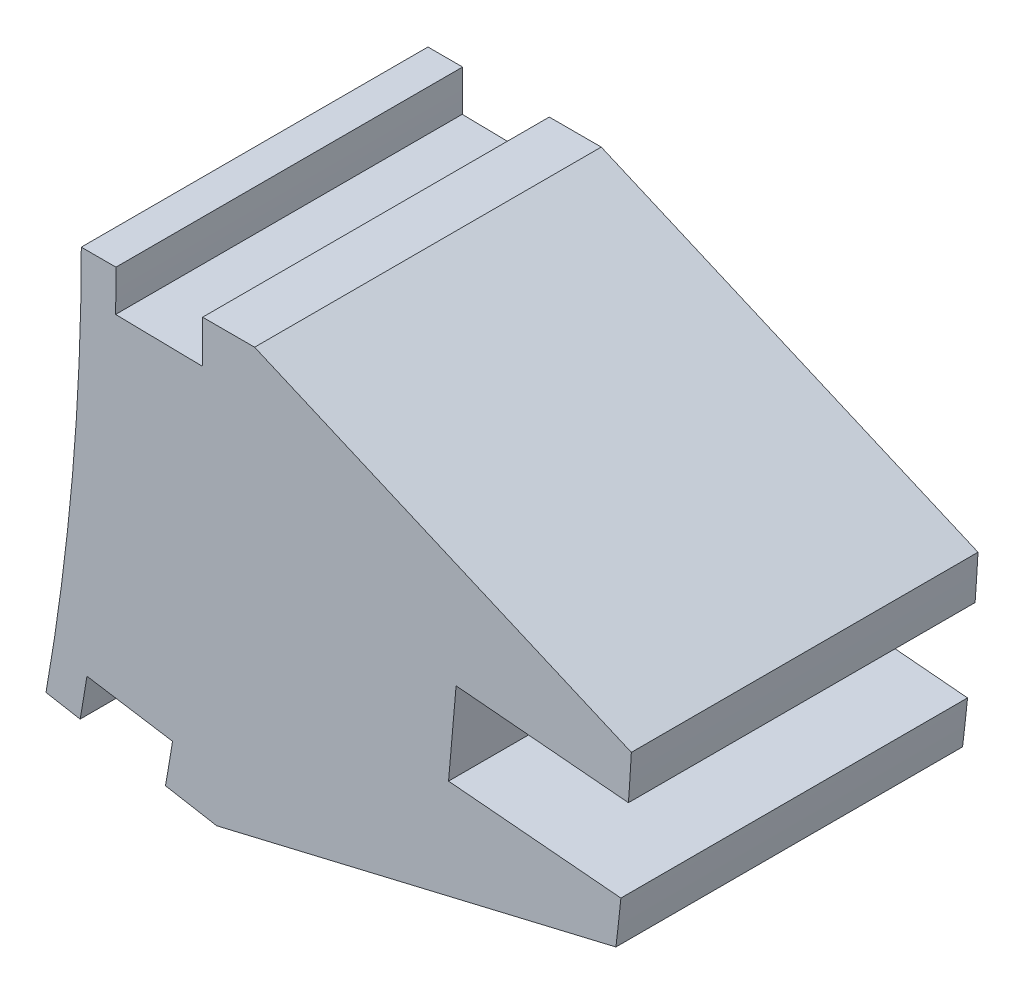
SolidWorks part; units mm, degrees
ref_plane "前视基准面" through (0, 0, 0) normal (0, 0, 1) x (1, 0, 0)
ref_plane "上视基准面" through (0, 0, 0) normal (0, 1, 0) x (1, 0, 0)
ref_plane "右视基准面" through (0, 0, 0) normal (1, 0, 0) x (0, 0, -1)
sketch "草图1" plane through (0, 0, 0) normal (0, 0, 1) x (1, 0, 0)
  line L0 (670, 0) -> (830, 0)
  line L1 (659.8212, -116.3443) -> (817.3904, -144.128)
  arc A0 (659.8212, -116.3443) -> (670, 0) centre (0, 0) ccw
  arc A1 (817.3904, -144.128) -> (830, 0) centre (0, 0) ccw
  dimension "D1" = 10
  dimension "D2" = 830
  dimension "D3" = 670
extrude "凸台-拉伸1" add sketch "草图1" along normal blind 100
sketch "草图2" plane through (0, 0, 100) normal (0, 0, 1) x (1, 0, 0)
  line L0 (0, 0) -> (826.8416, -72.3393) construction
  arc A0 (817.3904, -144.128) -> (830, 0) centre (0, 0) ccw construction
ref_plane "基准面1" through (0, 0, 0) normal (-0.0872, -0.9962, 0) x (0.9962, -0.0872, 0)
sketch "草图3" plane through (0, 0, 100) normal (0, 0, 1) x (1, 0, 0)
  line L0 (826.8416, -72.3393) -> (0, 0) construction
  line L1 (826.8416, -72.3393) -> (777.0319, -67.9815) construction
  line L2 (777.0319, -67.9815) -> (778.1213, -55.529)
  line L3 (778.1213, -55.529) -> (827.8373, -59.8786)
  line L4 (777.0319, -67.9815) -> (775.9424, -80.4339)
  line L5 (775.9424, -80.4339) -> (825.6584, -84.7835)
  arc A0 (817.3904, -144.128) -> (830, 0) centre (0, 0) ccw construction
  arc A2 (825.6584, -84.7835) -> (827.8373, -59.8786) centre (0, 0) ccw
  arc A3 (825.6584, -84.7835) -> (827.8373, -59.8786) centre (0, 0) ccw
  arc A4 (825.6584, -84.7835) -> (829.2756, -34.6705) centre (0, 0) ccw
  arc M6 (817.3904, -144.128) -> (830, 0) centre (0, 0) ccw
  dimension "D1" = 12.5
  dimension "D2" = 12.5
  dimension "D3" = 50
extrude "切除-拉伸1" cut sketch "草图3" against normal through all contours L4 L5 L3 L2 M6
sketch "草图4" plane through (0, 0, 100) normal (0, 0, 1) x (1, 0, 0)
  line L0 (776.1603, -77.9434) -> (825.97, -82.3012)
  line L1 (825.97, -82.3012) -> (821.6123, -132.1109)
  line L2 (821.6123, -132.1109) -> (771.8025, -127.7532)
  line L3 (771.8025, -127.7532) -> (776.1603, -77.9434)
  line L5 (0, 0) -> (826.8416, -72.3393) construction
  line L6 (771.8025, -127.7532) -> (825.97, -82.3012) construction
  line L7 (776.1603, -77.9434) -> (821.6123, -132.1109) construction
  point P6 (798.8863, -105.0272)
  dimension "D1" = 10
  dimension "D2" = 780
  dimension "D3" = 50
ref_plane "基准面2" through (-3.0505, -34.8668, 0) normal (-0.0872, -0.9962, 0) x (-0.9962, 0.0872, 0)
sketch "草图5" plane through (-3.0505, -34.8668, 0) normal (-0.0872, -0.9962, 0) x (-0.9962, 0.0872, 0)
  line L0 (-805, -100) -> (-810, -100)
  line L1 (-810, -100) -> (-818.6824, -50.7596)
  line L2 (-818.6824, -50.7596) -> (-818.6824, 0)
  line L3 (-818.6824, 0) -> (-805, 0)
  line L4 (-805, 0) -> (-805, -100)
  dimension "D1" = 5
  dimension "D2" = 50
  dimension "D3" = 100
  dimension "D4" = 100
sketch "草图6" plane through (0, 0, 0) normal (0, 0, -1) x (-1, 0, 0)
  line L1 (-669.6693, -118.0808) -> (-694.2895, -122.422)
  line L2 (-659.8212, -116.3443) -> (-817.3904, -144.128) construction
  line L4 (-671.6281, -106.3754) -> (-696.3203, -110.2863)
  line L5 (-671.6281, -106.3754) -> (0, 0) construction
  line L6 (-777.0319, -67.9815) -> (-667.4504, -58.3943) construction
  line L7 (-778.1213, -55.529) -> (-775.9424, -80.4339) construction
  line L8 (-679.8964, -11.8676) -> (0, 0) construction
  line L9 (-679.8964, -11.8676) -> (-704.8926, -12.3039)
  line L10 (-680, 0) -> (-705, 0)
  line L11 (-669.6693, -118.0808) -> (0, 0) construction
  arc A2 (-671.6281, -106.3754) -> (-669.6693, -118.0808) centre (0, 0) ccw
  arc A3 (-696.3203, -110.2863) -> (-694.2895, -122.422) centre (0, 0) ccw
  arc A5 (-670, 0) -> (-659.8212, -116.3443) centre (0, 0) ccw construction
  arc A6 (-704.8926, -12.3039) -> (-705, 0) centre (0, 0) cw
  arc A7 (-679.8964, -11.8676) -> (-680, 0) centre (0, 0) cw
  line M13 (-817.3904, -144.128) -> (-659.8212, -116.3443)
  arc M14 (-659.8212, -116.3443) -> (-670, 0) centre (0, 0) cw
  line M15 (-670, 0) -> (-830, 0)
  dimension "D1" = 25
  dimension "D2" = 705
  dimension "D4" = 1
extrude "切除-拉伸2" cut sketch "草图6" against normal through all contours L4 A3 M13 M14 | A6 L9 M14 M15
sketch "草图7" plane through (0, 0, 100) normal (0, 0, 1) x (1, 0, 0)
  line L0 (828.6751, -46.8786) -> (720, 0)
  line L2 (720, 0) -> (830, 0)
  line L3 (-118.3034, 10.3502) -> (118.3034, -10.3502) construction
  line L4 (709.0616, -125.0267) -> (817.3904, -144.128)
  line L5 (824.226, -97.7315) -> (709.0616, -125.0267)
  line L6 (830, 0) -> (705, 0) construction
  arc A1 (830, 0) -> (828.6751, -46.8786) centre (0, 0) cw
  arc A2 (817.3904, -144.128) -> (824.226, -97.7315) centre (0, 0) ccw
  arc A4 (827.8373, -59.8786) -> (830, 0) centre (0, 0) ccw construction
  point P0 (828.2496, -53.8755)
  point P3 (718.9024, 0)
  point P17 (0, 0)
  point P18 (0, 0)
  point P19 (0, 0)
  point P20 (0, 0)
  line M7 (694.2895, -122.422) -> (817.3904, -144.128)
  arc M8 (817.3904, -144.128) -> (825.6584, -84.7835) centre (0, 0) ccw
  arc M12 (827.8373, -59.8786) -> (830, 0) centre (0, 0) ccw
  line M13 (830, 0) -> (705, 0)
  dimension "D1" = 15
  dimension "D2" = 13
extrude "切除-拉伸3" cut sketch "草图7" against normal up to next contours L0 M12 M13 | L5 M8 M7
